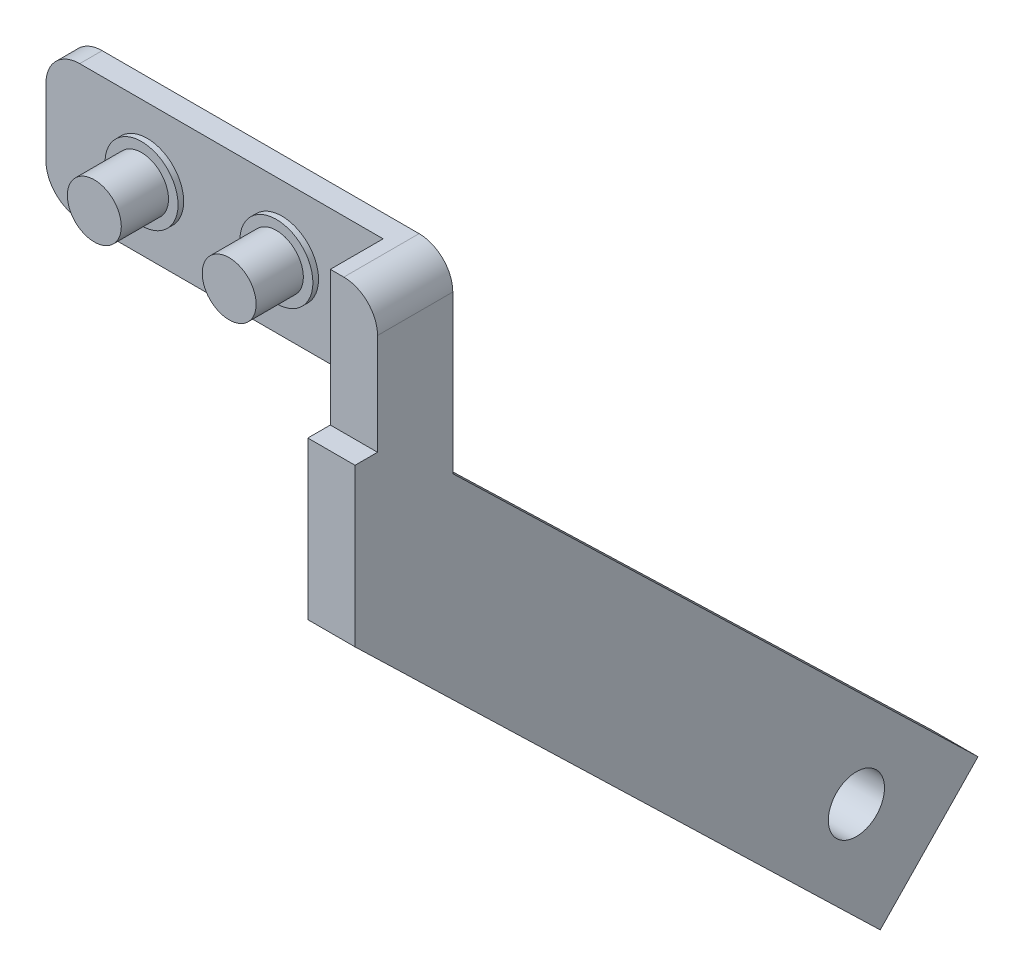
SolidWorks part; units mm, degrees
ref_plane "Plan de face" through (0, 0, 0) normal (0, 0, 1) x (1, 0, 0)
ref_plane "Plan de dessus" through (0, 0, 0) normal (0, 1, 0) x (1, 0, 0)
ref_plane "Plan de droite" through (0, 0, 0) normal (1, 0, 0) x (0, 0, -1)
sketch "Esquisse1" plane through (0, 0, 0) normal (0, 0, 1) x (1, 0, 0)
  line L1 (-12.8093, 4.9765) -> (17.1907, 4.9765)
  line L2 (-12.8093, 4.9765) -> (-12.8093, -7.0235)
  line L3 (-12.8093, -7.0235) -> (17.1907, -7.0235)
  line L4 (17.1907, 4.9765) -> (17.1907, -7.0235)
  dimension "D1" = 30
  dimension "D2" = 12
extrude "Boss.-Extru.1" add sketch "Esquisse1" along normal blind 2
sketch "Esquisse2" plane through (0, 0, 2) normal (0, 0, 1) x (1, 0, 0)
  line L0 (-6.0066, 4.9765) -> (-6.0066, -7.0235) construction
  line L1 (17.1907, 4.9765) -> (-12.8093, 4.9765) construction
  line L2 (-12.8093, -7.0235) -> (17.1907, -7.0235) construction
  line L3 (-3.8093, -1.0235) -> (8.1907, -1.0235) construction
  circle A0 centre (8.1907, -1.0235) radius 3.25
  circle A1 centre (-3.8093, -1.0235) radius 3.25
  point P10 (-6.0066, -1.0235)
  point P11 (2.1907, -1.0235)
  point P13 (2.1907, 4.9765)
  dimension "D1" = 6.5
  dimension "D2" = 12
extrude "Boss.-Extru.2" add sketch "Esquisse2" along normal blind 0.5
sketch "Esquisse3" plane through (0, 0, 2.5) normal (0, 0, 1) x (1, 0, 0)
  circle A0 centre (-3.8093, -1.0235) radius 2.4
  circle A1 centre (8.1907, -1.0235) radius 2.4
  dimension "D1" = 4.8
extrude "Boss.-Extru.3" add sketch "Esquisse3" along normal blind 4.2
sketch "Esquisse4" plane through (0, 0, 6.7) normal (0, 0, 1) x (1, 0, 0)
  circle A0 centre (8.1907, -1.0235) radius 5
  circle A1 centre (-3.8093, -1.0235) radius 5
  dimension "D1" = 10
sketch "Esquisse6" plane through (17.1907, 0, 0) normal (1, 0, 0) x (0, 0, -1)
  line L1 (0, 4.9765) -> (-6.7, 4.9765)
  line L2 (0, 4.9765) -> (0, -12.0235)
  line L3 (0, -12.0235) -> (-6.7, -12.0235)
  line L4 (-6.7, 4.9765) -> (-6.7, -12.0235)
  dimension "D1" = 5
extrude "Boss.-Extru.4" add sketch "Esquisse6" along normal blind 4.2
sketch "Esquisse8" plane through (0, 0, 6.7) normal (0, 0, 1) x (1, 0, 0)
  line L0 (21.3907, 4.9765) -> (21.3907, -12.0235) construction
  line L1 (17.1907, -12.0235) -> (21.3907, -12.0235)
  line L2 (17.1907, -12.0235) -> (17.1907, -7.0235)
  line L3 (17.1907, -7.0235) -> (21.3907, -7.0235)
  line L4 (21.3907, -12.0235) -> (21.3907, -7.0235)
extrude "Boss.-Extru.5" add sketch "Esquisse8" along normal blind 2
fillet "Congé1" radius 3 3 edges at (21.3907, 4.9765, 3.35) (-12.8093, 4.9765, 1) (-12.8093, -7.0235, 1)
sketch "Esquisse9" plane through (21.3907, 0, 0) normal (1, 0, 0) x (0, 0, -1)
  line L0 (-8.7, -12.0235) -> (-8.7, -21.0235)
  line L4 (0, -12.0235) -> (-8.7, -12.0235)
  line L5 (-8.7, -21.0235) -> (0, -12.0235)
  dimension "D2" = 9
extrude "Boss.-Extru.6" add sketch "Esquisse9" against normal up to vertex
sketch "Esquisse12" plane through (0, -5.808, -6.0083) normal (0, -0.695, -0.719) x (1, 0, 0)
  line L1 (21.3907, 21.1624) -> (17.1907, 21.1624)
  line L2 (21.3907, 21.1624) -> (21.3907, 8.6448)
  line L3 (21.3907, 8.6448) -> (17.1907, 8.6448)
  line L4 (17.1907, 21.1624) -> (17.1907, 8.6448)
extrude "Boss.-Extru.8" add sketch "Esquisse12" along normal blind 65
sketch "Esquisse13" plane through (17.1907, 0, 0) normal (-1, 0, 0) x (0, 0, 1)
  line L0 (-31.5633, -59.9448) -> (-40.2633, -50.9448) construction
  line L1 (-38.0342, -66.2) -> (8.7, -21.0235) construction
  line L2 (-46.7342, -57.2) -> (0, -12.0235) construction
  line L3 (-38.0342, -66.2) -> (-46.7342, -57.2) construction
  circle A0 centre (-35.9133, -55.4448) radius 2.5
  dimension "D1" = 5
  dimension "D2" = 9
extrude "Enlèv. mat.-Extru.2" cut sketch "Esquisse13" against normal up to vertex (4.2 mm away)
